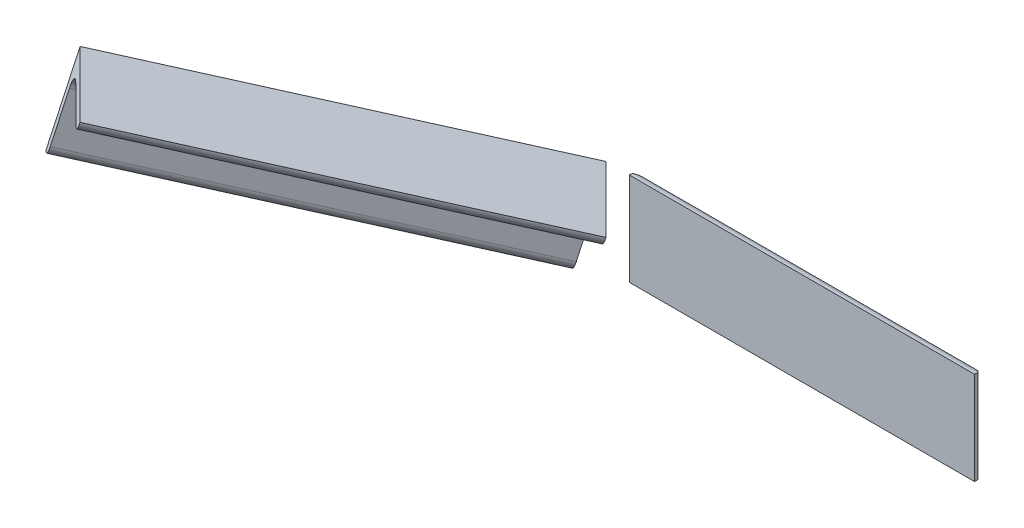
SolidWorks part; units mm, degrees
material "6061 Alloy"
ref_plane "Front Plane" through (0, 0, 0) normal (0, 0, 1) x (1, 0, 0)
ref_plane "Top Plane" through (0, 0, 0) normal (0, 1, 0) x (1, 0, 0)
ref_plane "Right Plane" through (0, 0, 0) normal (1, 0, 0) x (0, 0, -1)
sketch "Sketch19" plane through (0, 0, 0) normal (0, 1, 0) x (1, 0, 0)
  line L0 (0, 0) -> (53.4963, 53.4963) construction
  line L1 (100.6427, 82.6822) -> (24.3105, 6.35)
  line L2 (100.6427, 82.6822) -> (82.6822, 100.6427)
  line L3 (24.3105, 6.35) -> (6.35, 24.3105)
  line L4 (82.6822, 100.6427) -> (6.35, 24.3105)
  line L5 (100.6427, 82.6822) -> (6.35, 24.3105) construction
  line L6 (24.3105, 6.35) -> (82.6822, 100.6427) construction
  line L7 (0, 0) -> (71.0079, 0) construction
  dimension "D1" = 107.95
  dimension "D2" = 25.4
  dimension "D3" = 6.35
  dimension "45" = 45
sketch "Sketch3" plane through (0, 0, 0) normal (0, 1, 0) x (1, 0, 0)
  line L1 (6.35, 0) -> (100.6427, 0)
  line L2 (6.35, 0) -> (0, 0) construction
  point P1 (53.4963, 0)
  dimension "D1" = 6.35
other "Structural Member1"
ref_plane "Plane1" through (6.35, 0, 0) normal (1, 0, 0) x (0, 0, -1)
sketch "Sketch1" plane through (6.35, 0, 0) normal (1, 0, 0) x (0, 0, -1)
  line L0 (0, 0) -> (0, 25.4)
  line L1 (0, 25.4) -> (0.0051, 25.4)
  line L2 (3.175, 22.2301) -> (3.175, 7.9375)
  line L3 (7.9375, 3.175) -> (22.2301, 3.175)
  line L4 (25.4, 0.0051) -> (25.4, 0)
  line L5 (25.4, 0) -> (0, 0)
  arc A0 (25.4, 0.0051) -> (22.2301, 3.175) centre (22.2301, 0.0051) ccw
  arc A1 (0.0051, 25.4) -> (3.175, 22.2301) centre (0.0051, 22.2301) cw
  arc A2 (7.9375, 3.175) -> (3.175, 7.9375) centre (7.9375, 7.9375) cw
  point P10 (12.7, 0)
  point P14 (0, 12.7)
  point P15 (3.175, 12.7)
  point P16 (12.7, 3.175)
  point P17 (3.175, 25.4)
  point P18 (25.4, 3.175)
  point P19 (0, 0)
  dimension "D2" = 0.0051
  dimension "Radius_1" = 4.7625
  dimension "D1" = 3.175
  dimension "H_leg" = 25.4
sketch "Sketch12" plane through (0, 0, 0) normal (0, 1, 0) x (1, 0, 0)
  line L0 (0, 0) -> (35.4224, 35.4224) construction
  line L1 (6.35, 0) -> (100.6427, 0) construction
  line L2 (2.6941, -2.6941) -> (38.1164, 32.7283)
  line L7 (6.35, 25.4) -> (6.35, 0)
  line L8 (100.6427, 25.4) -> (6.35, 25.4)
  line L9 (100.6427, 0) -> (100.6427, 25.4)
  line L10 (6.35, 0) -> (100.6427, 0)
  line L11 (6.35, 25.4) -> (6.35, 0)
  line L12 (100.6427, 25.4) -> (6.35, 25.4)
  line L13 (100.6427, 0) -> (100.6427, 25.4)
  line L14 (6.35, 0) -> (100.6427, 0)
  dimension "D1" = 45
  dimension "D2" = 0
  dimension "D3" = 3.81
extrude "Cut-Extrude2" cut sketch "Sketch12" along normal through all
ref_plane "Plane6" through (0, 0, 0) normal (0.7071, 0, 0.7071) x (0.7071, 0, -0.7071)
sketch "Sketch15" plane through (0, 0, 0) normal (0.7071, 0, 0.7071) x (0.7071, 0, -0.7071)
  line L0 (0, 25.4) -> (-101.6, 52.6236)
  line L1 (0, 25.4) -> (-101.6, 25.4) construction
  line L3 (0, 0) -> (75.6553, 0) construction
  dimension "D1" = 101.6
  dimension "D2" = 15
  dimension "D3" = 25.4
other "Structural Member4"
ref_plane "Plane8" through (0, 25.4, 0) normal (-0.683, 0.2588, 0.683) x (-0.183, -0.9659, 0.183)
sketch "Sketch17" plane through (0, 25.4, 0) normal (-0.683, 0.2588, 0.683) x (-0.183, -0.9659, 0.183)
  line L0 (0, 0) -> (0, 25.4)
  line L1 (0, 25.4) -> (0.0051, 25.4)
  line L2 (3.175, 22.2301) -> (3.175, 7.9375)
  line L3 (7.9375, 3.175) -> (22.2301, 3.175)
  line L4 (25.4, 0.0051) -> (25.4, 0)
  line L5 (25.4, 0) -> (0, 0)
  arc A0 (25.4, 0.0051) -> (22.2301, 3.175) centre (22.2301, 0.0051) ccw
  arc A1 (0.0051, 25.4) -> (3.175, 22.2301) centre (0.0051, 22.2301) cw
  arc A2 (7.9375, 3.175) -> (3.175, 7.9375) centre (7.9375, 7.9375) cw
  point P10 (12.7, 0)
  point P14 (0, 12.7)
  point P15 (3.175, 12.7)
  point P16 (12.7, 3.175)
  point P17 (3.175, 25.4)
  point P18 (25.4, 3.175)
  point P19 (0, 0)
  dimension "D2" = 0.0051
  dimension "Radius_1" = 4.7625
  dimension "D1" = 3.175
  dimension "H_leg" = 25.4
ref_plane "Plane9" through (53.4963, 0, 0) normal (1, 0, 0) x (0, 0, -1)
mirror "Mirror2" about plane through (53.4963, 0, 0) normal (1, 0, 0) of "Cut-Extrude2"
sketch "Sketch20" plane through (0, 0, 0) normal (0, 1, 0) x (1, 0, 0)
  point P0 (53.4963, 53.4963)
